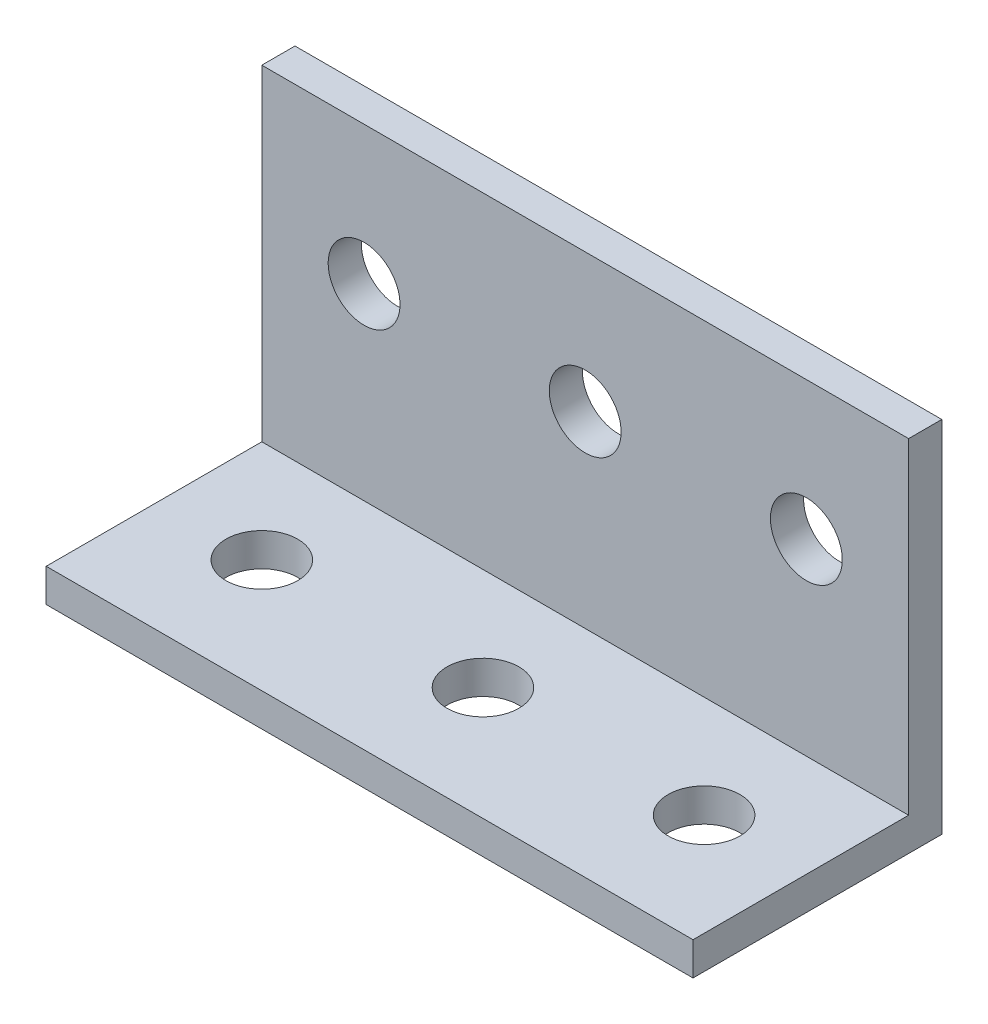
SolidWorks part; units mm, degrees
ref_plane "前视基准面" through (0, 0, 0) normal (0, 0, 1) x (1, 0, 0)
ref_plane "上视基准面" through (0, 0, 0) normal (0, 1, 0) x (1, 0, 0)
ref_plane "右视基准面" through (0, 0, 0) normal (1, 0, 0) x (0, 0, -1)
sketch "草图1" plane through (0, 0, 0) normal (0, 0, 1) x (1, 0, 0)
  line L1 (0, 0) -> (234, 0)
  line L2 (0, 0) -> (0, 130)
  line L3 (0, 130) -> (234, 130)
  line L4 (234, 0) -> (234, 130)
  dimension "D1" = 234
  dimension "D2" = 130
extrude "凸台-拉伸1" add sketch "草图1" along normal blind 90
sketch "草图2" plane through (0, 0, 0) normal (-1, 0, 0) x (0, 0, 1)
  line L0 (0, 130) -> (0, 0) construction
  line L1 (90, 130) -> (12, 130)
  line L2 (90, 130) -> (90, 12)
  line L3 (90, 12) -> (12, 12)
  line L4 (12, 130) -> (12, 12)
  line L5 (90, 0) -> (0, 0) construction
  dimension "D1" = 12
  dimension "D2" = 12
extrude "切除-拉伸1" cut sketch "草图2" against normal through all
sketch "草图3" plane through (0, 0, 0) normal (0, 0, -1) x (-1, 0, 0)
  line L0 (0, 0) -> (-234, 0) construction
  line L1 (-234, 0) -> (-234, 130) construction
  circle A0 centre (-197, 80) radius 13
  dimension "D1" = 26
  dimension "D2" = 80
  dimension "D3" = 37
extrude "切除-拉伸2" cut sketch "草图3" against normal through all
pattern_linear "阵列(线性)1" count 3 spacing 80 along (-1, 0, 0) of "切除-拉伸2"
sketch "草图4" plane through (0, 0, 0) normal (0, -1, 0) x (1, 0, 0)
  line L0 (0, 0) -> (234, 0) construction
  line L1 (0, 90) -> (0, 0) construction
  circle A0 centre (37, 49) radius 13
  dimension "D1" = 26
  dimension "D2" = 49
  dimension "D3" = 37
extrude "切除-拉伸3" cut sketch "草图4" against normal through all
pattern_linear "阵列(线性)2" count 3 spacing 80 along (1, 0, 0) of "切除-拉伸3"
